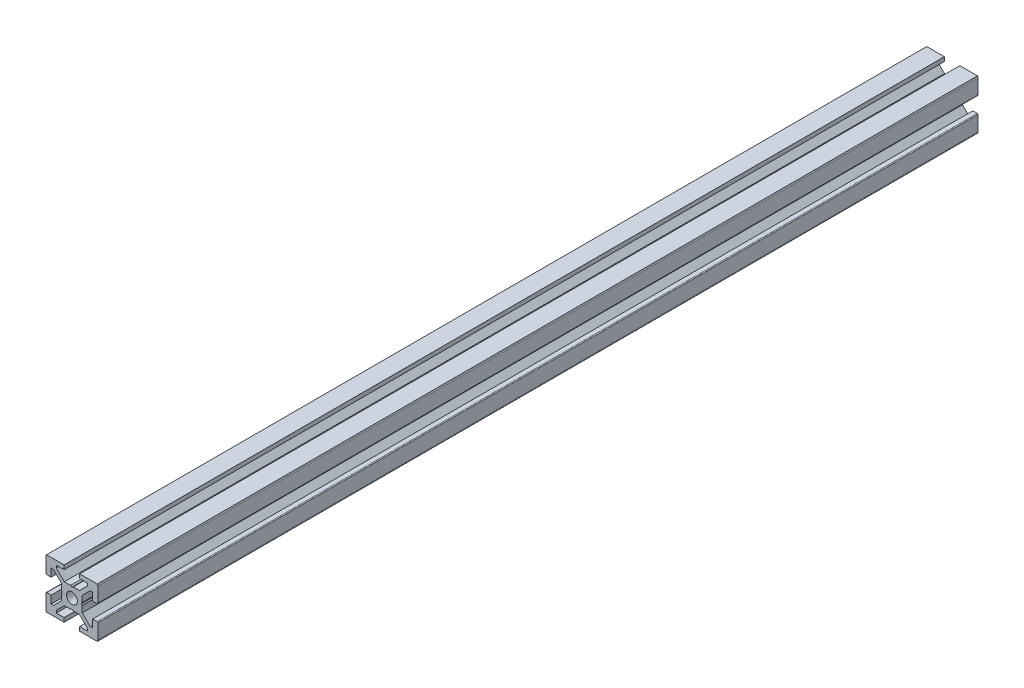
SolidWorks part; units mm, degrees
ref_plane "前视基准面" through (0, 0, 0) normal (0, 0, 1) x (1, 0, 0)
ref_plane "上视基准面" through (0, 0, 0) normal (0, 1, 0) x (1, 0, 0)
ref_plane "右视基准面" through (0, 0, 0) normal (1, 0, 0) x (0, 0, -1)
sketch "草图3" plane through (0, 0, 0) normal (0, 0, 1) x (1, 0, 0)
  line L0 (50, 62.1) -> (50, 37.9) construction
  line L1 (57.0607, 56) -> (54, 52.9393)
  line L2 (58, 56) -> (58, 53)
  line L3 (56, 57.0607) -> (52.9393, 54)
  line L4 (42, 56) -> (42, 53)
  line L5 (42.9393, 56) -> (46, 52.9393)
  line L6 (44, 57.0607) -> (47.0607, 54)
  line L7 (60, 59) -> (60, 53.3)
  line L8 (40, 59) -> (40, 53.3)
  line L9 (37.5, 50) -> (62.5, 50) construction
  line L10 (57.0607, 44) -> (54, 47.0607)
  line L11 (53, 40.4) -> (59.8, 40.4)
  line L12 (42.9393, 44) -> (46, 47.0607)
  line L13 (44, 42) -> (47, 42)
  line L14 (44, 42.9393) -> (47.0607, 46)
  line L15 (40.2, 40.4) -> (47, 40.4)
  line L16 (42, 44) -> (42, 47)
  line L17 (44, 42.9393) -> (44, 42)
  line L18 (40, 46.7) -> (40, 41)
  line L19 (42, 44) -> (42.9393, 44)
  line L20 (40.3, 47) -> (42, 47)
  line L21 (40.3, 53) -> (42, 53)
  line L22 (47, 40.4) -> (47, 42)
  line L23 (56, 42.9393) -> (56, 42)
  line L24 (56, 42) -> (53, 42)
  line L25 (53, 40.4) -> (53, 42)
  line L26 (56, 42.9393) -> (52.9393, 46)
  line L27 (58, 44) -> (58, 47)
  line L28 (60, 46.7) -> (60, 41)
  line L29 (57.0607, 44) -> (58, 44)
  line L30 (59.7, 47) -> (58, 47)
  line L31 (59.7, 53) -> (58, 53)
  line L32 (53, 59.6) -> (59.8, 59.6)
  line L33 (44, 58) -> (47, 58)
  line L34 (40.2, 59.6) -> (47, 59.6)
  line L35 (42, 56) -> (42.9393, 56)
  line L36 (44, 58) -> (44, 57.0607)
  line L37 (47, 59.6) -> (47, 58)
  line L38 (53, 59.6) -> (53, 58)
  line L39 (56, 58) -> (53, 58)
  line L40 (56, 58) -> (56, 57.0607)
  line L41 (57.0607, 56) -> (58, 56)
  line L45 (46, 52.9393) -> (46, 50.5196)
  line L46 (54, 52.9393) -> (54, 50.5196)
  line L47 (47.0607, 54) -> (49.4804, 54)
  line L48 (47.0607, 46) -> (49.4804, 46)
  line L49 (50, 53.7) -> (49.4804, 54)
  line L50 (50, 53.7) -> (50.5196, 54)
  line L51 (50.5196, 54) -> (52.9393, 54)
  line L52 (46.3, 50) -> (46, 49.4804)
  line L53 (46.3, 50) -> (46, 50.5196)
  line L54 (50, 46.3) -> (50.5196, 46)
  line L55 (50, 46.3) -> (49.4804, 46)
  line L56 (53.7, 50) -> (54, 50.5196)
  line L57 (53.7, 50) -> (54, 49.4804)
  line L58 (54, 49.4804) -> (54, 47.0607)
  line L59 (50.5196, 46) -> (52.9393, 46)
  line L60 (46, 49.4804) -> (46, 47.0607)
  arc A0 (40.3, 47) -> (40, 46.7) centre (40.3, 46.7) ccw
  arc A1 (40, 53.3) -> (40.3, 53) centre (40.3, 53.3) ccw
  circle A2 centre (50, 50) radius 2.1
  arc A3 (60, 46.7) -> (59.7, 47) centre (59.7, 46.7) ccw
  arc A4 (59.7, 53) -> (60, 53.3) centre (59.7, 53.3) ccw
  arc A5 (60, 59) -> (59.8, 59.6) centre (59, 59) ccw
  arc A6 (40.2, 59.6) -> (40, 59) centre (41, 59) ccw
  arc A7 (40, 41) -> (40.2, 40.4) centre (41, 41) ccw
  arc A8 (59.8, 40.4) -> (60, 41) centre (59, 41) ccw
extrude "凸台-拉伸1" add sketch "草图3" along normal blind 340
